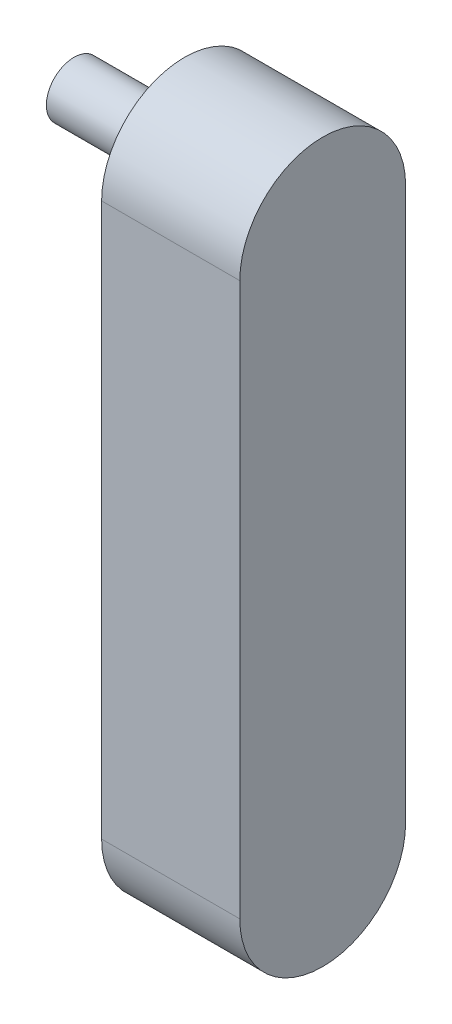
SolidWorks part; units mm, degrees
ref_plane "Front Plane" through (0, 0, 0) normal (0, 0, 1) x (1, 0, 0)
ref_plane "Top Plane" through (0, 0, 0) normal (0, 1, 0) x (1, 0, 0)
ref_plane "Right Plane" through (0, 0, 0) normal (1, 0, 0) x (0, 0, -1)
sketch "Sketch1" plane through (0, 0, 0) normal (1, 0, 0) x (0, 0, -1)
  line L0 (0, 127) -> (0, -127) construction
  line L1 (0, 55) -> (0, -55) construction
  line L2 (38.1, 127) -> (38.1, -127)
  line L3 (-38.1, 127) -> (-38.1, -127)
  arc A0 (38.1, 127) -> (-38.1, 127) centre (0, 127) ccw
  arc A1 (-38.1, -127) -> (38.1, -127) centre (0, -127) ccw
  point P5 (0, 0)
extrude "Boss-Extrude1" add sketch "Sketch1" along normal blind 63.5 contours L3 A1 L2 A0
sketch "Sketch2" plane through (0, 0, 0) normal (1, 0, 0) x (0, 0, -1)
  circle A0 centre (0, -127) radius 13.97
  dimension "D1" = 27.94
extrude "Cut-Extrude1" cut sketch "Sketch2" along normal blind 48.26
sketch "Sketch3" plane through (0, 0, 0) normal (1, 0, 0) x (0, 0, -1)
  circle A0 centre (0, 127) radius 12.7
  dimension "D1" = 25.4
extrude "Boss-Extrude2" add sketch "Sketch3" against normal blind 50.8
